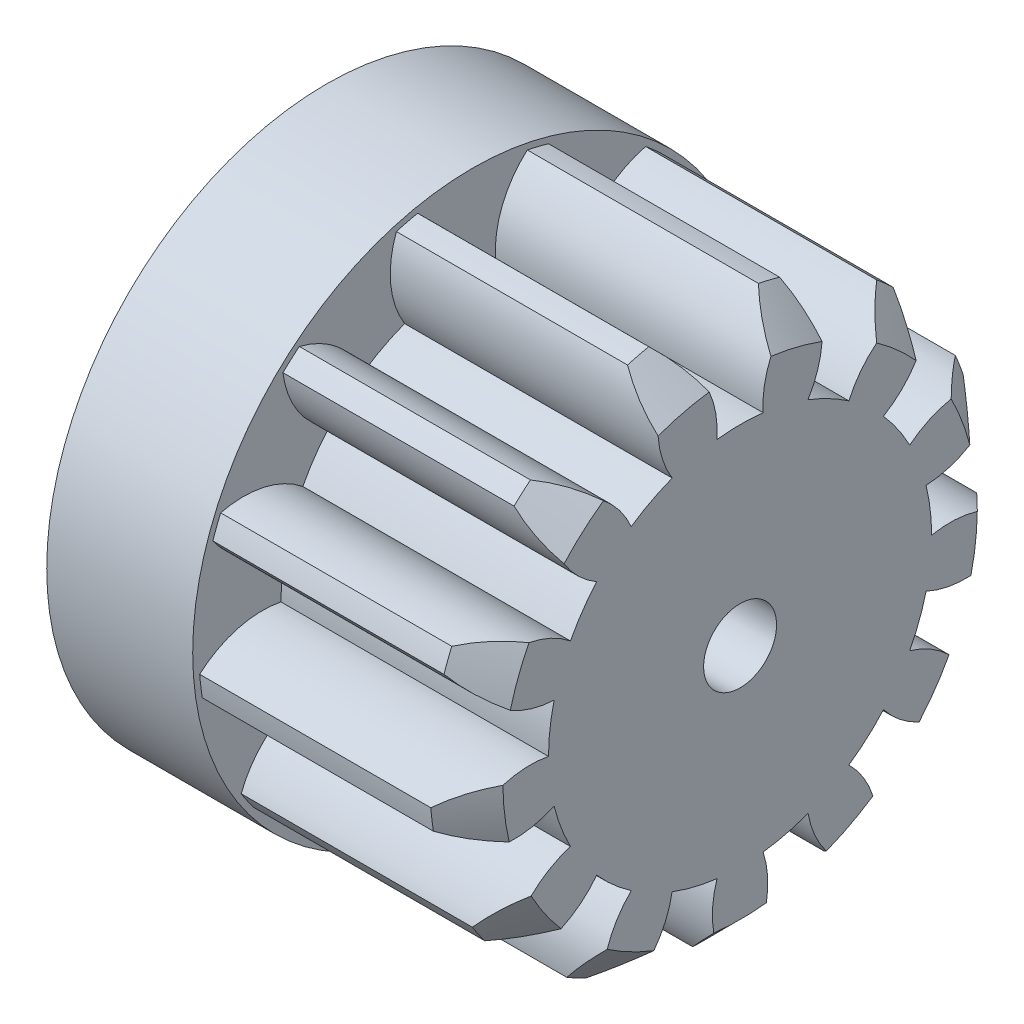
SolidWorks part; units mm, degrees
material "ABS"
ref_plane "Plane1" through (0, 0, 0) normal (0, 0, 1) x (1, 0, 0)
ref_plane "Plane2" through (0, 0, 0) normal (0, 1, 0) x (1, 0, 0)
ref_plane "Plane3" through (0, 0, 0) normal (1, 0, 0) x (0, 0, -1)
sketch "HoldingSke" plane through (0, 0, 0) normal (0, 1, 0) x (1, 0, 0)
  line L0 (0, 0) -> (0.6496, -0.15)
  line L1 (-15, 0) -> (100, 0) construction
  line L2 (0, 0) -> (-2.1039, 2.3779)
  line L3 (0, 0) -> (-11.863, 4.5341)
  line L4 (0, 0) -> (8.4147, 1.9427)
  line L5 (0, 0) -> (-46.8476, -17.4728)
  line L6 (0, 0) -> (-9.1186, -6.1523)
  line L7 (-2.1039, 2.3779) -> (8.6586, 51.2059)
  line L8 (-76.2, 54.61) -> (-75.7, 54.61)
  line L9 (-67.7845, 28.3722) -> (-49.3413, 33.142)
  line L10 (-76.2, 71.12) -> (104.1128, 71.12)
  line L11 (0, 0) -> (-11, 0)
  line L12 (-76.2, 101.6) -> (-76.147, 101.6)
  line L13 (24.9733, 27.94) -> (52.9518, 28.4284)
  line L14 (24.9733, 27.94) -> (24.9743, 27.94)
  line L15 (24.9733, 27.94) -> (100.4006, 29.5858)
  line L16 (-63.627, -1.5) -> (-12.827, -1.5)
  circle A0 centre (0, 0) radius 1.5
  circle A1 centre (0, 0) radius 7.874
  circle A2 centre (0, 0) radius 37.5
  circle A3 centre (0, 0) radius 1.5
  dimension "MHD" = 15.748
  dimension "Hub_dia" = 75
  dimension "Bore" = 3
  dimension "MBD" = 3
  dimension "Num_teeth" = 13
  dimension "Pitch_radius" = 180.3128
  dimension "Pitch" = 0.6667
  dimension "Width" = 11
  dimension "Overall_len" = 50
  dimension "Show_teeth" = 13
  dimension "Thickness" = 11
  dimension "OAL" = 50.0001
  dimension "T_dim" = 0.5
  dimension "Ap" = 14.5
  dimension "H" = 19.05
  dimension "Backlash" = 0.053
  dimension "Addendum_fac" = 1
  dimension "Dedendum_fac" = 1.25
  dimension "Clearance_fac" = 0.25
  dimension "Dedendum_add" = 0.001
  dimension "Module" = 1.5
sketch "BasProSke" plane through (0, 0, 0) normal (0, 1, 0) x (1, 0, 0)
  line L0 (-10, 0) -> (60, 0) construction
  line L1 (0, 0) -> (0, 11.25)
  line L2 (0, 0) -> (11, 0)
  line L3 (11, 0) -> (11, 11.25)
  line L4 (11, 11.25) -> (0, 11.25)
  dimension "Diameter" = 22.5
  dimension "Thickness" = 11
revolve "Base-Revolve" add sketch "BasProSke" angle 360 about L0
sketch "TooCutSke" plane through (0, 0, 0) normal (1, 0, 0) x (0, 0, -1)
  line L1 (0, 0) -> (0, 107) construction
  line L2 (0, 0) -> (-1.2679, 9.6672) construction
  line L3 (0, 0) -> (-4.6378, 18.8163) construction
  line L4 (-1.2679, 9.6672) -> (-2.3189, 9.4082) construction
  arc A0 (0.9514, 7.8163) -> (-0.9514, 7.8163) centre (0, 0) ccw
  arc A1 (2.2774, 11.043) -> (-2.2774, 11.043) centre (0, 0) ccw
  circle A2 centre (0, 0) radius 9.75 construction
  circle A3 centre (0, 0) radius 9.4394 construction
  arc A4 (-0.9514, 7.8163) -> (-2.2774, 11.043) centre (-4.8408, 8.1037) ccw
  arc A5 (2.2774, 11.043) -> (0.9514, 7.8163) centre (4.8408, 8.1037) ccw
  dimension "Root_dia" = 15.748
  dimension "Overcut_dia" = 22.5508
  dimension "Pitch_dia" = 19.5
  dimension "Base_dia" = 18.8789
  dimension "Flank_rad" = 3.9
  dimension "Half_ang" = 13.846
  dimension "Half_CT" = 1.0825
extrude "ToothCut" cut sketch "TooCutSke" along normal through all
fillet "Breaks" [suppressed] radius 0.03
fillet "RootFillets" [suppressed] radius 0.376
pattern_circular "TeethCuts" count 13 every 27.692 about axis through (-10, 0, 0) along (1, 0, 0) of "ToothCut", "RootFillets", "Breaks"
sketch "HubNeaOneSke" plane through (0, 0, 0) normal (-1, 0, 0) x (0, 0, 1)
  circle A0 centre (0, 0) radius 7.874
  dimension "Diameter" = 15.748
extrude "HubNearOne" [suppressed] add sketch "HubNeaOneSke" along normal blind 39.0001
sketch "HubNeaBotSke" plane through (0, 0, 0) normal (-1, 0, 0) x (0, 0, 1)
  circle A0 centre (0, 0) radius 7.874
  dimension "Diameter" = 15.748
extrude "HubNearBoth" [suppressed] add sketch "HubNeaBotSke" along normal blind 19.5
ref_plane "FarPln" through (11, 0, 0) normal (1, 0, 0) x (0, 0, -1)
sketch "HubFarSke" plane through (11, 0, 0) normal (1, 0, 0) x (0, 0, -1)
  circle A0 centre (0, 0) radius 7.874
  dimension "Diameter" = 15.748
extrude "HubFar" [suppressed] add sketch "HubFarSke" along normal blind 19.5
sketch "BorSke" plane through (0, 0, 0) normal (1, 0, 0) x (0, 0, -1)
  circle A0 centre (0, 0) radius 1.5
  dimension "Diameter" = 3
extrude "Bore" cut sketch "BorSke" along normal mid plane 100.0001
sketch "KeySke" plane through (0, 0, 0) normal (1, 0, 0) x (0, 0, -1)
  line L0 (-0.6, 0) -> (-0.6, 2)
  line L1 (-0.6, 2) -> (0.6, 2)
  line L2 (0.6, 2) -> (0.6, 0)
  line L3 (0, 0) -> (0, 34) construction
  line L4 (-0.6, 0) -> (0.6, 0)
  dimension "Offset" = 2
  dimension "Width" = 1.2
extrude "Keyway" [suppressed] cut sketch "KeySke" along normal mid plane 100.0001
pattern_circular "Keyway2" [suppressed] count 2 every 90 about axis through (-10, 0, 0) along (1, 0, 0)
sketch "Sketch1" plane through (11, 0, 0) normal (1, 0, 0) x (0, 0, -1)
  circle A0 centre (0, 0) radius 9.75
  dimension "D1" = 19.5
sketch "Sketch2" plane through (0, 0, 0) normal (-1, 0, 0) x (0, 0, 1)
  circle A0 centre (0, 0) radius 11.5
  dimension "D1" = 23
extrude "Boss-Extrude1" add sketch "Sketch2" along normal blind 6
sketch "Sketch4" plane through (-6, 0, 0) normal (-1, 0, 0) x (0, 0, 1)
  circle A0 centre (0, 0) radius 3.225
  dimension "D1" = 6.45
extrude "Cut-Extrude1" cut sketch "Sketch4" against normal blind 3.8
sketch "Sketch5" plane through (-6, 0, 0) normal (-1, 0, 0) x (0, 0, 1)
  circle A0 centre (0, 0) radius 1.5
  dimension "D1" = 3
extrude "Cut-Extrude2" cut sketch "Sketch5" against normal up to surface (6 mm away) up to face at (0, 0, 11.5)
sketch "Sketch6" plane through (0, 0, 0) normal (0, 1, 0) x (1, 0, 0)
  line L0 (0, -0.9514) -> (0, 0.9514) construction
  circle A0 centre (-2.5, 0) radius 1.725
  point P2 (0, 0)
  dimension "D1" = 3.45
  dimension "D2" = 2.5
extrude "Cut-Extrude3" cut sketch "Sketch6" against normal blind 11.8
sketch "Sketch7" plane through (-6, 0, 0) normal (-1, 0, 0) x (0, 0, 1)
  line L0 (-2.85, -1.3707) -> (-2.85, -5.825)
  line L1 (-2.85, -5.825) -> (2.85, -5.825)
  line L2 (2.85, -5.825) -> (2.85, -1.3707)
  line L3 (2.85, -1.3707) -> (1.6987, -1.3707)
  line L4 (1.6987, -1.3707) -> (1.6987, 0)
  line L5 (1.6987, 0) -> (-1.6987, 0)
  line L6 (-1.6987, 0) -> (-1.6987, -1.3707)
  line L7 (-1.6987, -1.3707) -> (-2.85, -1.3707)
  line L8 (0, 0) -> (0, -5.825) construction
  line L9 (-2.85, -3.225) -> (2.85, -3.225) construction
  line L10 (1.6987, -2.7414) -> (1.6987, 0) construction
  line L11 (-1.6987, 0) -> (-1.6987, -2.7414) construction
  circle A0 centre (0, 0) radius 3.225 construction
  dimension "D1" = 2.6
  dimension "D2" = 5.7
extrude "Cut-Extrude4" cut sketch "Sketch7" against normal blind 6.8
chamfer "Chamfer1" distance 1.5 angle 45 13 edges at (11, -9.9614, 5.2281) (11, -6.3907, 9.2586) (11, -1.356, 11.168) (11, 3.9893, 10.5189) (11, 8.4207, 7.4601) (11, 10.9231, 2.6923) (11, 10.9231, -2.6923) (11, 8.4207, -7.4601) (11, 3.9893, -10.5189) (11, -1.356, -11.168) (11, -6.3907, -9.2586) (11, -9.9614, -5.2281) (11, -11.25, 0)
equation "' \"Module@HoldingSke\" = 6.35"
equation "' \"Num_teeth@HoldingSke\" = 12"
equation "' \"Ap@HoldingSke\" =  20"
equation "' \"Width@HoldingSke\" = 0.5 * 25.4"
equation "' \"Hub_dia@HoldingSke\"= 1 * 25.4"
equation "' \"Overall_len@HoldingSke\" = 1.0 * 25.4"
equation "' \"Bore@HoldingSke\" = 0.75 * 25.4"
equation "' \"T_dim@HoldingSke\" = 0.1 * 25.4"
equation "' \"Width@KeySke\" = 0.25 * 25.4"
equation "' \"Show_teeth@HoldingSke\" = 13"
equation "' \"Backlash@HoldingSke\" = 0.009 * 25.4"
equation "' \"Addendum_fac@HoldingSke\" = 1.0"
equation "' \"Dedendum_fac@HoldingSke\" = 1.25"
equation "' \"Dedendum_add@HoldingSke\" = 0.00005 * 25.4"
equation "' \"Clearance_fac@HoldingSke\" = 0.25"
equation "\"Pitch@HoldingSke\" = 1 / \"Module@HoldingSke\""
equation "\"Overcut_dia@TooCutSke\" = (\"Num_teeth@HoldingSke\" + 2 * \"Addendum_fac@HoldingSke\") / \"Pitch@HoldingSke\" + 0.002 * 25.4"
equation "\"Pitch_dia@TooCutSke\" = \"Num_teeth@HoldingSke\" / \"Pitch@HoldingSke\""
equation "\"Base_dia@TooCutSke\" = \"Num_teeth@HoldingSke\" / \"Pitch@HoldingSke\" * cos((\"Ap@HoldingSke\"  * 3.14159265 / 180))"
equation "\"Root_dia@TooCutSke\" = (\"Num_teeth@HoldingSke\" + 2) / \"Pitch@HoldingSke\" - 2 * (\"Addendum_fac@HoldingSke\" + \"Dedendum_fac@HoldingSke\") / \"Pitch@HoldingSke\" - \"Dedendum_add@HoldingSke\" * 2"
equation "\"Half_ang@TooCutSke\" = 180 / \"Num_teeth@HoldingSke\""
equation "\"Half_CT@TooCutSke\" = \"Num_teeth@HoldingSke\" / \"Pitch@HoldingSke\" * sin((3.14159265 / 2 / \"Num_teeth@HoldingSke\")) / 2 - 7 * \"Backlash@HoldingSke\" / 4"
equation "\"Flank_rad@TooCutSke\" = \"Num_teeth@HoldingSke\" / \"Pitch@HoldingSke\" / 5"
equation "\"Radius@RootFillets\" = \"Clearance_fac@HoldingSke\" / \"Pitch@HoldingSke\" + \"Dedendum_add@HoldingSke\""
equation "\"Break_rad@Breaks\" = 0.02 / \"Pitch@HoldingSke\""
equation "\"Thickness@HoldingSke\" = \"Width@HoldingSke\""
equation "\"OAL@HoldingSke\" = \"Thickness@HoldingSke\""
equation "\"MHD@HoldingSke\" = (\"Num_teeth@HoldingSke\" + 2) / \"Pitch@HoldingSke\" - 2 * (\"Addendum_fac@HoldingSke\" + \"Dedendum_fac@HoldingSke\")  / \"Pitch@HoldingSke\" - \"Dedendum_add@HoldingSke\" * 2"
equation "\"MBD@HoldingSke\" = (\"Num_teeth@HoldingSke\" + 2) / \"Pitch@HoldingSke\" - 2 * (\"Addendum_fac@HoldingSke\" + \"Dedendum_fac@HoldingSke\")  / \"Pitch@HoldingSke\" - \"Dedendum_add@HoldingSke\" * 2 - 0.002 * 25.4"
equation "\"MHD@HoldingSke\" = ((sgn( \"MHD@HoldingSke\" - \"Hub_dia@HoldingSke\" )-1)*( \"MHD@HoldingSke\" - \"Hub_dia@HoldingSke\" ))/-2+ \"Hub_dia@HoldingSke\""
equation "\"MBD@HoldingSke\" = ((sgn( \"MBD@HoldingSke\" - \"Bore@HoldingSke\" )-1)*( \"MBD@HoldingSke\" - \"Bore@HoldingSke\" ))/-2+ \"Bore@HoldingSke\""
equation "\"OAL@HoldingSke\" = ((sgn( \"OAL@HoldingSke\" - \"Overall_len@HoldingSke\" )+1)*( \"OAL@HoldingSke\" - \"Overall_len@HoldingSke\" ))/2 + \"Overall_len@HoldingSke\" + 0.000002 * 25.4"
equation "\"Num_teeth@TeethCuts\" = int( \"Show_teeth@HoldingSke\" ) + 1"
equation "\"Num_teeth@TeethCuts\" = ((sgn( \"Num_teeth@TeethCuts\" - \"Num_teeth@HoldingSke\" )-1)*( \"Num_teeth@TeethCuts\" - \"Num_teeth@HoldingSke\" ))/-2+ \"Num_teeth@HoldingSke\""
equation "\"Num_teeth@TeethCuts\" = ((sgn( \"Num_teeth@TeethCuts\" - 2.0)+1)*( \"Num_teeth@TeethCuts\" - 2.0))/2 +2.0"
equation "\"Angle@TeethCuts\" = 360.0 / \"Num_teeth@HoldingSke\""
equation "\"Diameter@BasProSke\" = (\"Num_teeth@HoldingSke\" + 2 * \"Addendum_fac@HoldingSke\") / \"Pitch@HoldingSke\""
equation "\"Thickness@BasProSke\"  = \"Thickness@HoldingSke\""
equation "' \"Fillet_rad@BasProSke\" =  \"Thickness@HoldingSke\" * 0.05"
equation "\"MHD@HoldingSke\" = ((sgn( \"MHD@HoldingSke\" - \"Root_dia@TooCutSke\" )-1)*( \"MHD@HoldingSke\" - \"Root_dia@TooCutSke\" ))/-2+ \"Root_dia@TooCutSke\""
equation "\"Diameter@HubNeaOneSke\" = \"MHD@HoldingSke\""
equation "\"Length@HubNearOne\" = \"OAL@HoldingSke\" - \"Thickness@BasProSke\""
equation "\"Diameter@HubNeaBotSke\" = \"MHD@HoldingSke\""
equation "\"Length@HubNearBoth\" = ( \"OAL@HoldingSke\" - \"Thickness@BasProSke\" ) / 2.0"
equation "\"Thickness@FarPln\" = \"Thickness@BasProSke\""
equation "\"Diameter@HubFarSke\" = \"MHD@HoldingSke\""
equation "\"Length@HubFar\" = ( \"OAL@HoldingSke\" - \"Thickness@BasProSke\" ) / 2.0"
equation "\"Diameter@BorSke\" = \"MBD@HoldingSke\""
equation "\"D1@Bore\" = \"OAL@HoldingSke\" * 2.0"
equation "\"D1@Keyway\" = \"OAL@HoldingSke\" * 2.0"
equation "\"Offset@KeySke\" = \"T_dim@HoldingSke\" + \"MBD@HoldingSke\" / 2.0"
equation "\"D1@Sketch4\"=6.00mm+\"print_free@Parameters@Parameters.SLDPRT\""
equation "\"D1@Sketch6\"=3.00mm+\"print_free@Parameters@Parameters.SLDPRT\""
equation "\"D1@Sketch7\"=2.4mm+\"print_fit@Parameters@Parameters.SLDPRT\""
equation "\"D2@Sketch7\"=5.5+\"print_fit@Parameters@Parameters.SLDPRT\""
